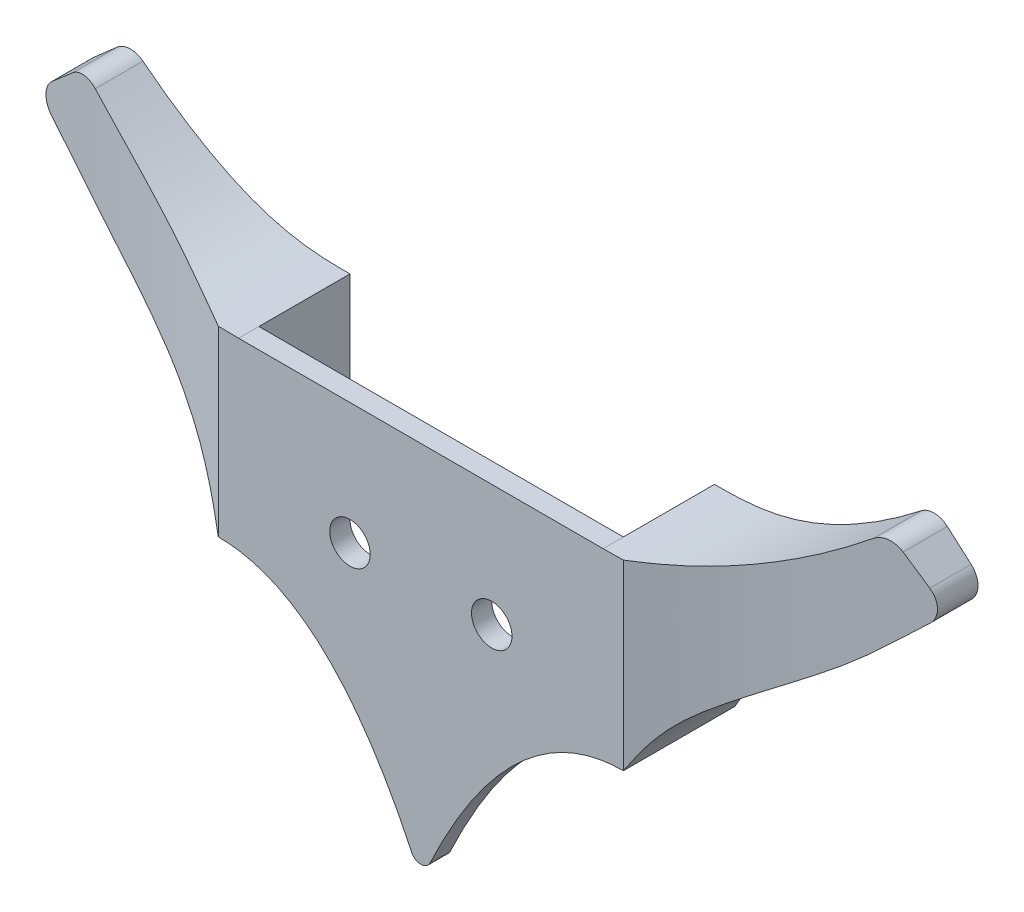
SolidWorks part; units mm, degrees
ref_plane "Front" through (0, 0, 0) normal (0, 0, 1) x (1, 0, 0)
ref_plane "Top" through (0, 0, 0) normal (0, 1, 0) x (1, 0, 0)
ref_plane "Right" through (0, 0, 0) normal (1, 0, 0) x (0, 0, -1)
sketch "Sketch1" plane through (0, 0, 0) normal (0, 0, 1) x (1, 0, 0)
  line L0 (0, -4.5) -> (45, -4.5) construction
  line L1 (0, 22.5) -> (45, 22.5) construction
  line L2 (0, 22.5) -> (0, -22.5) construction
  line L3 (0, -22.5) -> (45, -22.5) construction
  line L4 (45, 22.5) -> (45, -22.5) construction
  line L5 (0, 13.5) -> (45, 13.5) construction
  line L6 (0, 13.5) -> (0, -22.5)
  line L7 (0.9043, -21.927) -> (10.8303, -0.9055) construction
  line L8 (18, 22.5) -> (18, -22.5) construction
  line L9 (20, 22.5) -> (20, -22.5) construction
  line L10 (39.7392, 22.5) -> (45, 17.8822)
  line L11 (0, 13.5) -> (18, 13.5)
  arc A0 (0, -22.5) -> (0.9043, -21.927) centre (0, -21.5) ccw
  spline S0 degree 2 poles (0.9043, -21.927) (9.1331, -4.5) (20, -4.5) knots 0 0 0 1 1 1
  spline S1 degree 3 poles (18, 13.5) (22.5939, 13.5) (28.7382, 13.5118) (39.7392, 22.5) knots 0 0 0 0 1 1 1 1
  spline S2 degree 3 poles (20, -4.5) (22.4421, -0.0878) (24.4175, 1.3647) (37.3118, 10.2913) (39.0926, 12.3668) (45, 17.8822) knots 0 0 0 0 0.423319 0.523319 1 1 1 1
  dimension "D5" = 1
  dimension "D1" = 9
  dimension "D2" = 45
  dimension "D3" = 18
  dimension "D4" = 18
  dimension "D6" = 18
  dimension "D7" = 2
  dimension "D8" = 7
extrude "Main" add sketch "Sketch1" along normal blind 11
fillet "Fillet1" radius 2 2 edges at (45, 17.8822, 5.5) (39.7392, 22.5, 5.5)
sketch "Sketch2" plane through (0, 0, 0) normal (0, 0, -1) x (-1, 0, 0)
  line L1 (0, -22.5) -> (-18, -22.5)
  line L2 (0, -22.5) -> (0, 13.5)
  line L3 (0, 13.5) -> (-18, 13.5)
  line L4 (-18, -22.5) -> (-18, 13.5)
  line L5 (0, 13.5) -> (0, -22.5) construction
  line L6 (-18, 13.5) -> (0, 13.5) construction
  dimension "D1" = 18
extrude "Cut-Extrude1" cut sketch "Sketch2" against normal blind 9
ref_plane "Plane1" through (0, -22.5, 0) normal (0, 1, 0) x (1, 0, 0)
sketch "Sketch4" plane through (0, -22.5, 0) normal (0, 1, 0) x (1, 0, 0)
  line L0 (20, -11) -> (44.0248, -11)
  line L1 (44.0248, -11) -> (44.0248, -4)
  line L3 (44.0248, -11) -> (44.0248, 0) construction
  spline S0 degree 3 poles (20, -11) (28.6352, -6.133) (33.0861, -5.2843) (44.0248, -4) knots 0 0 0 0 1 1 1 1
  dimension "D1" = 7
extrude "Cut-Extrude3" cut sketch "Sketch4" along normal through all
sketch "Sketch5" plane through (0, 0, 11) normal (0, 0, 1) x (1, 0, 0)
  line L0 (18, 13.5) -> (0, 13.5) construction
  line L2 (18, 13.5) -> (18, -4.651) construction
  circle A0 centre (7, 1.5) radius 2
  dimension "D1" = 12
  dimension "D2" = 11
  dimension "D3" = 4
extrude "Cut-Extrude4" cut sketch "Sketch5" against normal through all
mirror "Mirror1" about plane through (0, 13.5, 11) normal (1, 0, 0) of bodies 105 103
